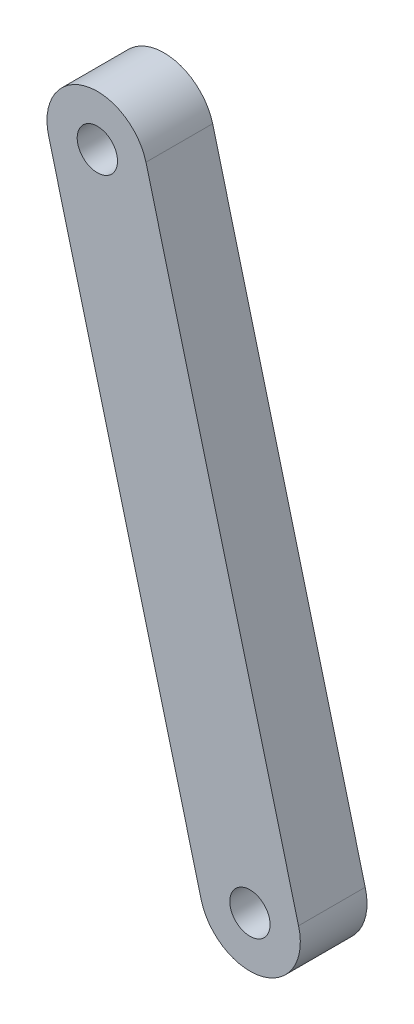
SolidWorks part; units mm, degrees
ref_plane "Front Plane" through (0, 0, 0) normal (0, 0, 1) x (1, 0, 0)
ref_plane "Top Plane" through (0, 0, 0) normal (0, 1, 0) x (1, 0, 0)
ref_plane "Right Plane" through (0, 0, 0) normal (1, 0, 0) x (0, 0, -1)
sketch "Sketch1" plane through (0, 0, 0) normal (0, 0, 1) x (1, 0, 0)
  line L0 (-26.4604, -117.2903) -> (-18.8881, -146.3189)
  line L1 (-21.6371, -115.9727) -> (-14.0648, -145.0013)
  line L2 (-14.0648, -145.0013) -> (-18.8881, -146.3189) construction
  circle A1 centre (-24.0488, -116.6315) radius 1
  arc A2 (-18.9025, -146.2633) -> (-14.0648, -145.0013) centre (-16.4764, -145.6601) ccw
  circle A3 centre (-16.4764, -145.6601) radius 1
  arc A4 (-21.6371, -115.9727) -> (-26.4604, -117.2903) centre (-24.0488, -116.6315) ccw
  dimension "D2" = 2
  dimension "D1" = 30
extrude "Boss-Extrude1" add sketch "Sketch1" along normal blind 3.31 contours L2 L1 A4 L0 A3 A1 | A2 L2 A3
